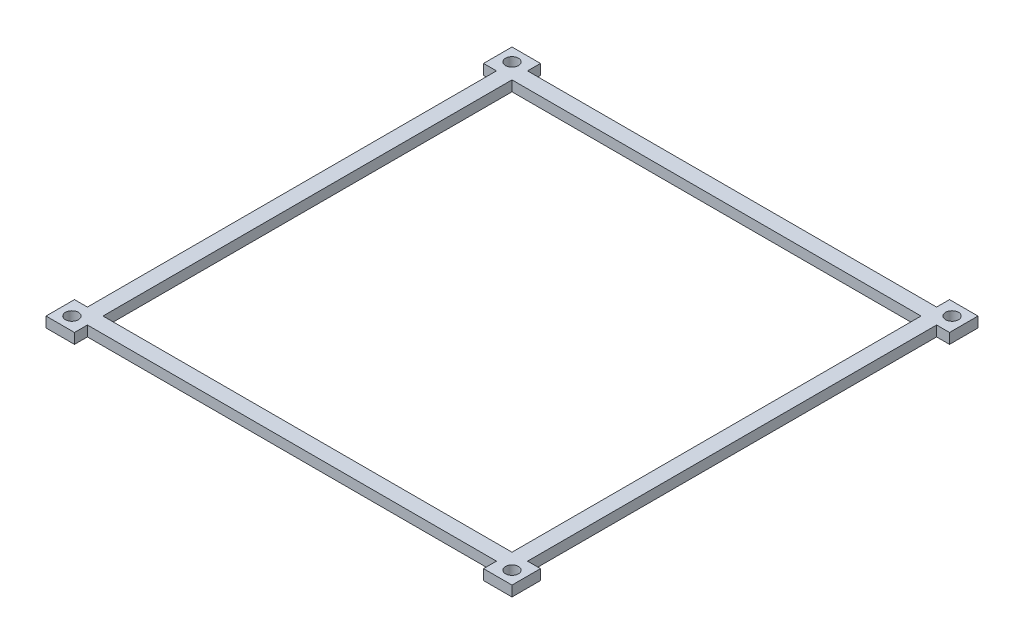
SolidWorks part; units mm, degrees
ref_plane "Alzado" through (0, 0, 0) normal (0, 0, 1) x (1, 0, 0)
ref_plane "Planta" through (0, 0, 0) normal (0, 1, 0) x (1, 0, 0)
ref_plane "Vista lateral" through (0, 0, 0) normal (1, 0, 0) x (0, 0, -1)
sketch "Croquis1" plane through (0, 0, 0) normal (0, 1, 0) x (1, 0, 0)
  line L0 (100, 15) -> (100, 0) construction
  line L1 (0, 0) -> (200, 0)
  line L2 (0, 0) -> (0, 200)
  line L3 (0, 200) -> (200, 200)
  line L4 (200, 0) -> (200, 200)
  line L5 (15, 15) -> (185, 15) construction
  line L6 (15, 15) -> (15, 185) construction
  line L7 (15, 185) -> (185, 185) construction
  line L8 (185, 15) -> (185, 185) construction
  line L9 (185, 100) -> (200, 100) construction
  circle A0 centre (15, 185) radius 2.5
  circle A1 centre (185, 185) radius 2.5
  circle A2 centre (185, 15) radius 2.5
  circle A3 centre (15, 15) radius 2.5
  dimension "D3" = 5
  dimension "D1" = 200
  dimension "D2" = 170
extrude "Saliente-Extruir1" add sketch "Croquis1" along normal blind 4
sketch "Croquis2" plane through (0, 4, 0) normal (0, 1, 0) x (1, 0, 0)
  line L0 (0, 200) -> (200, 0) construction
  line L2 (21, 21) -> (179, 21)
  line L3 (21, 21) -> (21, 179)
  line L4 (21, 179) -> (179, 179)
  line L5 (179, 21) -> (179, 179)
  line L6 (21, 21) -> (179, 179) construction
  line L7 (21, 179) -> (179, 21) construction
  point P4 (100, 100)
  dimension "D1" = 158
extrude "Cortar-Extruir1" cut sketch "Croquis2" against normal blind 10
sketch "Croquis3" plane through (0, 4, 0) normal (0, 1, 0) x (1, 0, 0)
  line L0 (0, 0) -> (200, 0) construction
  line L1 (0, 200) -> (0, 0) construction
  line L2 (200, 200) -> (0, 200) construction
  line L3 (200, 0) -> (200, 200) construction
  line L4 (0, 0) -> (200, 0)
  line L5 (0, 200) -> (0, 0)
  line L6 (200, 200) -> (0, 200)
  line L7 (200, 0) -> (200, 200)
  line L8 (10, 10) -> (190, 10)
  line L9 (190, 10) -> (190, 190)
  line L10 (190, 190) -> (10, 190)
  line L11 (10, 190) -> (10, 10)
  dimension "D1" = 10
extrude "Cortar-Extruir2" cut sketch "Croquis3" against normal blind 10
sketch "Croquis4" plane through (0, 4, 0) normal (0, 1, 0) x (1, 0, 0)
  line L0 (190, 190) -> (10, 190) construction
  line L1 (21, 190) -> (179, 190)
  line L2 (21, 190) -> (21, 185)
  line L3 (21, 185) -> (179, 185)
  line L4 (179, 190) -> (179, 185)
  line L5 (100, 179) -> (100, 185) construction
  line L6 (179, 179) -> (21, 179) construction
  line L7 (21, 100) -> (179, 100) construction
  line L8 (21, 179) -> (21, 21) construction
  line L9 (179, 21) -> (179, 179) construction
  line L10 (100, 179) -> (100, 21) construction
  line L11 (21, 21) -> (179, 21) construction
  line L12 (190, 179) -> (185, 179)
  line L13 (190, 179) -> (190, 21)
  line L14 (190, 21) -> (185, 21)
  line L15 (185, 179) -> (185, 21)
  line L16 (179, 10) -> (179, 15)
  line L17 (179, 10) -> (21, 10)
  line L18 (21, 10) -> (21, 15)
  line L19 (179, 15) -> (21, 15)
  line L20 (10, 21) -> (15, 21)
  line L21 (10, 21) -> (10, 179)
  line L22 (10, 179) -> (15, 179)
  line L23 (15, 21) -> (15, 179)
  dimension "D1" = 5
  dimension "D2" = 158
extrude "Cortar-Extruir3" cut sketch "Croquis4" against normal blind 10
